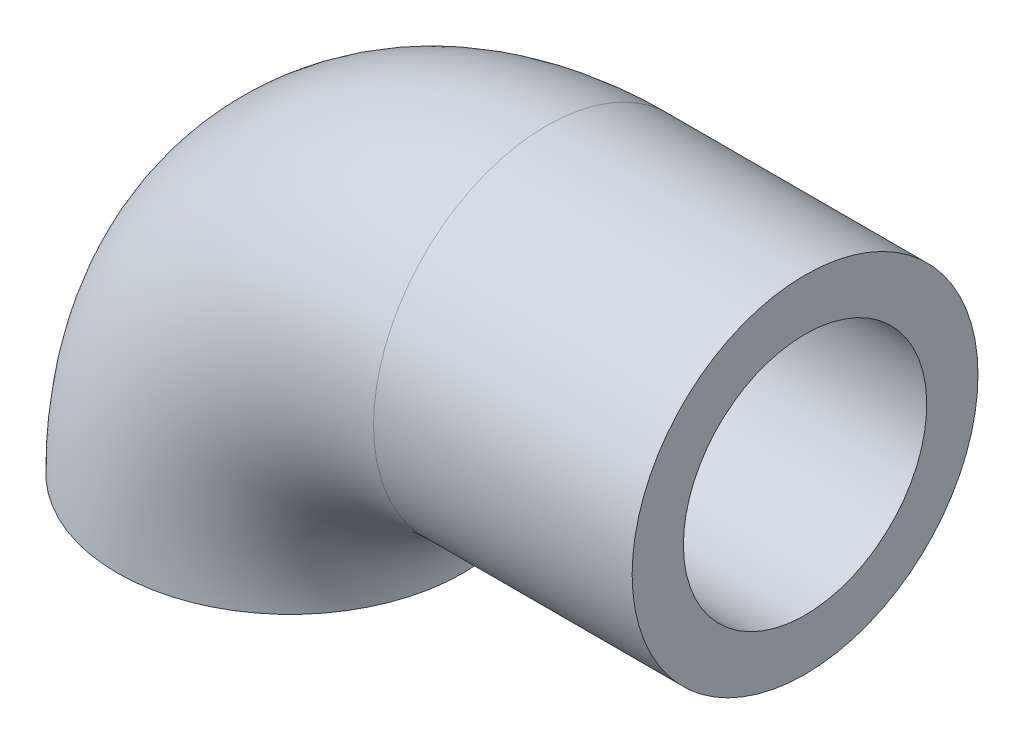
SolidWorks part; units mm, degrees
material "ABS PC"
ref_plane "Front Plane" through (0, 0, 0) normal (0, 0, 1) x (1, 0, 0)
ref_plane "Top Plane" through (0, 0, 0) normal (0, 1, 0) x (1, 0, 0)
ref_plane "Right Plane" through (0, 0, 0) normal (1, 0, 0) x (0, 0, -1)
sketch "Sketch1" plane through (0, 0, 0) normal (0, 0, 1) x (1, 0, 0)
  line L0 (55, 0) -> (-55, 0) construction
  line L1 (0, -55) -> (0, 55) construction
  line L2 (10, 10) -> (20.0949, 10)
  arc A0 (0, 0) -> (10, 10) centre (10, 0) cw
  dimension "D1" = 10
  dimension "D2" = 10
sketch "Sketch2" plane through (0, 0, 0) normal (0, 1, 0) x (1, 0, 0)
  circle A0 centre (0, 0) radius 6.75
  circle A1 centre (0, 0) radius 4.75
  dimension "D1" = 9.5
  dimension "D2" = 2
sweep "Sweep1" add profiles "Sketch2" path "Sketch1"
